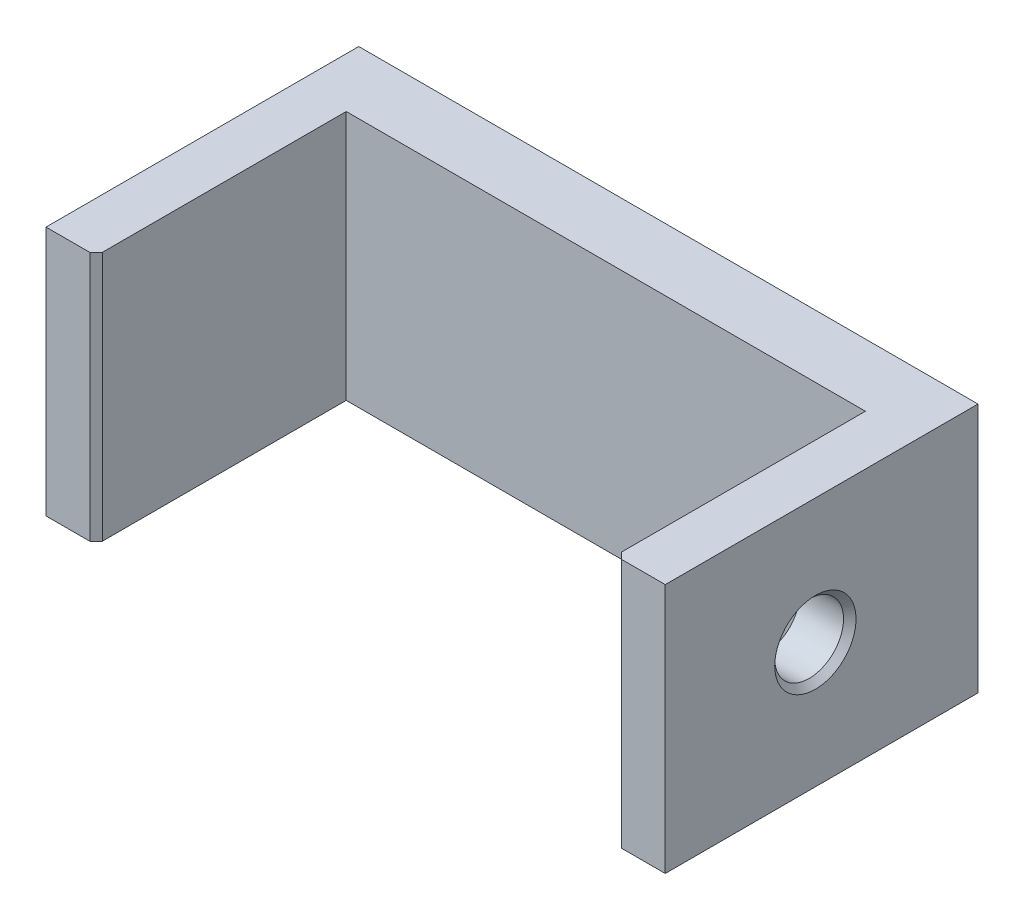
SolidWorks part; units mm, degrees
ref_plane "前视基准面" through (0, 0, 0) normal (0, 0, 1) x (1, 0, 0)
ref_plane "上视基准面" through (0, 0, 0) normal (0, 1, 0) x (1, 0, 0)
ref_plane "右视基准面" through (0, 0, 0) normal (1, 0, 0) x (0, 0, -1)
sketch "草图1" plane through (0, 0, 0) normal (0, 0, 1) x (1, 0, 0)
  line L1 (0, 0) -> (49.5, 0)
  line L2 (0, 0) -> (0, -20)
  line L3 (0, -20) -> (49.5, -20)
  line L4 (49.5, 0) -> (49.5, -20)
  dimension "D1" = 20
  dimension "D2" = 49.5
extrude "凸台-拉伸1" add sketch "草图1" along normal blind 5
sketch "草图3" plane through (0, 0, 5) normal (0, 0, 1) x (1, 0, 0)
  line L0 (49.5, 0) -> (0, 0) construction
  line L1 (49.5, -20) -> (45.5, -20)
  line L2 (49.5, -20) -> (49.5, 0)
  line L3 (49.5, 0) -> (45.5, 0)
  line L4 (45.5, -20) -> (45.5, 0)
  line L5 (0, -20) -> (49.5, -20) construction
  line L6 (0, 0) -> (4, 0)
  line L7 (0, 0) -> (0, -20)
  line L8 (0, -20) -> (4, -20)
  line L9 (4, 0) -> (4, -20)
  dimension "D1" = 4
  dimension "D2" = 4
extrude "凸台-拉伸2" add sketch "草图3" along normal blind 20
chamfer "倒角1" distance 0.5 angle 45 2 edges at (45.5, -10, 25) (4, -10, 25)
sketch "草图4" plane through (49.5, 0, 0) normal (1, 0, 0) x (0, 0, -1)
  line L0 (-25, -20) -> (-25, 0) construction
  line L1 (-25, 0) -> (0, 0) construction
  circle A0 centre (-13, -10) radius 2.75
  dimension "D1" = 5.5
  dimension "D2" = 12
  dimension "D3" = 10
extrude "切除-拉伸1" cut sketch "草图4" against normal blind 20
chamfer "倒角2" distance 0.5 angle 45 1 edges at (49.5, -10, 10.25)
